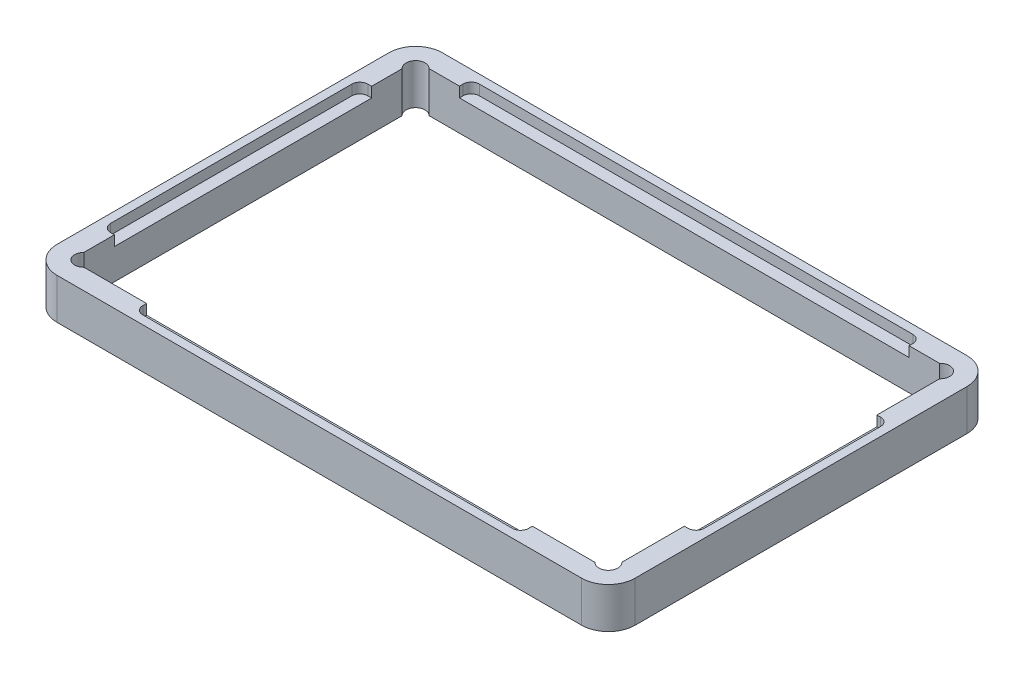
SolidWorks part; units mm, degrees
ref_plane "Front" through (0, 0, 0) normal (0, 0, 1) x (1, 0, 0)
ref_plane "Top" through (0, 0, 0) normal (0, 1, 0) x (1, 0, 0)
ref_plane "Right" through (0, 0, 0) normal (1, 0, 0) x (0, 0, -1)
sketch "Sketch1" plane through (0, 0, 0) normal (0, 1, 0) x (1, 0, 0)
  line L0 (-45, 0) -> (45, 0) construction
  line L1 (-45, 30) -> (45, 30) construction
  line L2 (-45, 30) -> (-45, -30) construction
  line L3 (-45, -30) -> (45, -30) construction
  line L4 (45, 30) -> (45, -30) construction
  line L5 (0, -30) -> (0, 30) construction
  line L6 (41.825, 26.825) -> (41.825, -26.825) construction
  line L7 (-41.825, -26.825) -> (41.825, -26.825) construction
  line L8 (-41.825, 26.825) -> (-41.825, -26.825) construction
  line L9 (-41.825, 26.825) -> (41.825, 26.825) construction
  line L10 (40.825, 25.825) -> (40.825, -25.825) construction
  line L11 (-40.825, -25.825) -> (40.825, -25.825) construction
  line L12 (-40.825, 25.825) -> (-40.825, -25.825) construction
  line L13 (-40.825, 25.825) -> (40.825, 25.825) construction
  line L14 (40.825, 21.65) -> (45, 21.65) construction
  line L15 (40.825, -21.65) -> (45, -21.65) construction
  line L16 (36.65, -25.825) -> (36.65, -30) construction
  line L17 (-36.65, -25.825) -> (-36.65, -30) construction
  line L18 (-40.825, -21.65) -> (-45, -21.65) construction
  line L19 (-36.65, 25.825) -> (-36.65, 30) construction
  line L20 (-40.825, 21.65) -> (-45, 21.65) construction
  line L21 (36.65, 25.825) -> (36.65, 30) construction
  line L22 (40.825, -25.825) -> (41.825, -25.825) construction
  circle A0 centre (-40.825, -25.825) radius 1 construction
  circle A1 centre (40.825, -25.825) radius 1 construction
  circle A2 centre (40.825, 25.825) radius 1 construction
  circle A3 centre (-40.825, 25.825) radius 1 construction
  circle A4 centre (40.825, -25.825) radius 4.175 construction
  circle A5 centre (40.825, 25.825) radius 4.175 construction
  circle A6 centre (-40.825, 25.825) radius 4.175 construction
  circle A7 centre (-40.825, -25.825) radius 4.175 construction
  dimension "D1" = 90
  dimension "D2" = 60
  dimension "D4" = 1
  dimension "D3" = 3.175
sketch "Sketch2" plane through (0, 0, 0) normal (0, 1, 0) x (1, 0, 0)
  line L0 (-45, 30) -> (-45, -30) construction
  line L1 (-45, -30) -> (45, -30) construction
  line L2 (45, 30) -> (45, -30) construction
  line L3 (-45, 30) -> (45, 30) construction
  line L12 (-41.825, -25.825) -> (-41.825, 25.825)
  line L13 (-40.825, 26.825) -> (40.825, 26.825)
  line L14 (41.825, 25.825) -> (41.825, -25.825)
  line L15 (40.825, -26.825) -> (-40.825, -26.825)
  line L16 (-45, 25.825) -> (-45, -25.825)
  line L17 (-40.825, -30) -> (40.825, -30)
  line L18 (45, 25.825) -> (45, -25.825)
  line L19 (-40.825, 30) -> (40.825, 30)
  circle A0 centre (40.825, 25.825) radius 4.175 construction
  circle A1 centre (40.825, 25.825) radius 1 construction
  circle A2 centre (-40.825, 25.825) radius 4.175 construction
  circle A3 centre (-40.825, 25.825) radius 1 construction
  arc A6 (45, 25.825) -> (40.825, 30) centre (40.825, 25.825) ccw
  arc A7 (41.825, 25.825) -> (40.825, 26.825) centre (40.825, 25.825) ccw
  arc A8 (-40.825, 30) -> (-45, 25.825) centre (-40.825, 25.825) ccw
  arc A9 (-40.825, 26.825) -> (-41.825, 25.825) centre (-40.825, 25.825) ccw
  circle A12 centre (-40.825, -25.825) radius 1 construction
  circle A13 centre (40.825, -25.825) radius 1 construction
  arc A14 (-41.825, -25.825) -> (-40.825, -26.825) centre (-40.825, -25.825) ccw
  arc A15 (40.825, -26.825) -> (41.825, -25.825) centre (40.825, -25.825) ccw
  arc A17 (-45, -25.825) -> (-40.825, -30) centre (-40.825, -25.825) ccw
  arc A18 (40.825, -30) -> (45, -25.825) centre (40.825, -25.825) ccw
extrude "Boss-Extrude3" add sketch "Sketch2" along normal blind 6.35
sketch "Sketch5" plane through (0, 0, 0) normal (0, -1, 0) x (1, 0, 0)
  circle A0 centre (-40.825, 25.825) radius 1.4224 construction
  circle A1 centre (-40.825, 25.825) radius 1.4224
  circle A2 centre (40.825, 25.8149) radius 1.4732 construction
  circle A3 centre (40.825, -25.825) radius 1.4732 construction
  circle A4 centre (-40.825, -25.8136) radius 1.4732 construction
  circle A5 centre (40.825, 25.8149) radius 1.4732
  circle A6 centre (40.825, -25.825) radius 1.4732
  circle A7 centre (-40.825, -25.8136) radius 1.4732
extrude "Cut-Extrude2" cut sketch "Sketch5" against normal through all
sketch "Sketch7" plane through (0, 6.35, 0) normal (0, 1, 0) x (1, 0, 0)
  line L0 (-33.7539, 28.4074) -> (33.7432, 28.4074) construction
  line L1 (34.7432, 26.0649) -> (34.7432, 27.4074) construction
  line L2 (-34.7539, 26.0649) -> (34.7432, 26.0649) construction
  line L3 (-34.7539, 27.4074) -> (-34.7539, 26.0649) construction
  line L4 (-41.075, 19.7216) -> (-42.4125, 19.7216) construction
  line L5 (-41.075, 19.7216) -> (-41.075, -19.8236) construction
  line L6 (-41.075, -19.8236) -> (-42.4125, -19.8236) construction
  line L7 (-43.4125, -18.8236) -> (-43.4125, 18.7216) construction
  line L8 (41.075, 14.7331) -> (42.4125, 14.7331) construction
  line L9 (43.4125, 13.7331) -> (43.4125, -13.7432) construction
  line L10 (42.4125, -14.7432) -> (41.075, -14.7432) construction
  line L11 (41.075, -14.7432) -> (41.075, 14.7331) construction
  line L13 (29.7526, -26.0851) -> (-29.8135, -26.0851) construction
  line L14 (-29.8135, -26.0851) -> (-29.8135, -27.4176) construction
  line L15 (-28.8135, -28.4176) -> (28.7526, -28.4176) construction
  line L16 (29.7526, -26.0851) -> (29.7526, -27.4176) construction
  line L18 (-41.075, -0.051) -> (41.075, -0.0051) construction
  line L19 (-0.0053, 26.0649) -> (-0.0304, -26.0851) construction
  line L20 (-35.0039, 27.4074) -> (-35.0039, 25.8149)
  line L21 (-35.0039, 25.8149) -> (34.9932, 25.8149)
  line L22 (34.9932, 25.8149) -> (34.9932, 27.4074)
  line L23 (-33.7539, 28.6574) -> (33.7432, 28.6574)
  line L24 (-43.6625, -18.8236) -> (-43.6625, 18.7216)
  line L25 (-40.825, -20.0736) -> (-42.4125, -20.0736)
  line L26 (-40.825, 19.9716) -> (-40.825, -20.0736)
  line L27 (-40.825, 19.9716) -> (-42.4125, 19.9716)
  line L28 (40.825, 14.9831) -> (42.4125, 14.9831)
  line L29 (43.6625, 13.7331) -> (43.6625, -13.7432)
  line L30 (42.4125, -14.9932) -> (40.825, -14.9932)
  line L31 (40.825, -14.9932) -> (40.825, 14.9831)
  line L32 (-28.8135, -28.6676) -> (28.7526, -28.6676)
  line L33 (-30.0635, -25.8351) -> (-30.0635, -27.4176)
  line L34 (30.0026, -25.8351) -> (-30.0635, -25.8351)
  line L35 (30.0026, -25.8351) -> (30.0026, -27.4176)
  arc A0 (33.7432, 28.4074) -> (34.7432, 27.4074) centre (33.7432, 27.4074) cw construction
  arc A1 (-33.7539, 28.4074) -> (-34.7539, 27.4074) centre (-33.7539, 27.4074) ccw construction
  arc A2 (-42.4125, 19.7216) -> (-43.4125, 18.7216) centre (-42.4125, 18.7216) ccw construction
  arc A3 (-42.4125, -19.8236) -> (-43.4125, -18.8236) centre (-42.4125, -18.8236) cw construction
  arc A4 (-29.8135, -27.4176) -> (-28.8135, -28.4176) centre (-28.8135, -27.4176) ccw construction
  arc A5 (29.7526, -27.4176) -> (28.7526, -28.4176) centre (28.7526, -27.4176) cw construction
  arc A6 (43.4125, -13.7432) -> (42.4125, -14.7432) centre (42.4125, -13.7432) cw construction
  arc A7 (42.4125, 14.7331) -> (43.4125, 13.7331) centre (42.4125, 13.7331) cw construction
  arc A8 (33.7432, 28.6574) -> (34.9932, 27.4074) centre (33.7432, 27.4074) cw
  arc A9 (-33.7539, 28.6574) -> (-35.0039, 27.4074) centre (-33.7539, 27.4074) ccw
  arc A10 (-42.4125, 19.9716) -> (-43.6625, 18.7216) centre (-42.4125, 18.7216) ccw
  arc A11 (-42.4125, -20.0736) -> (-43.6625, -18.8236) centre (-42.4125, -18.8236) cw
  arc A12 (42.4125, 14.9831) -> (43.6625, 13.7331) centre (42.4125, 13.7331) cw
  arc A13 (43.6625, -13.7432) -> (42.4125, -14.9932) centre (42.4125, -13.7432) cw
  arc A14 (30.0026, -27.4176) -> (28.7526, -28.6676) centre (28.7526, -27.4176) cw
  arc A15 (-30.0635, -27.4176) -> (-28.8135, -28.6676) centre (-28.8135, -27.4176) ccw
  dimension "D3" = 1
  dimension "D5" = 52.15
  dimension "D10" = 1
  dimension "D11" = 1
  dimension "D14" = 1
  dimension "D1" = 67.4971
  dimension "D2" = 69.4971
  dimension "D4" = 1.3426
  dimension "D6" = 82.15
  dimension "D7" = 37.5452
  dimension "D8" = 39.5452
  dimension "D9" = 1.3375
  dimension "D12" = 59.5661
  dimension "D13" = 57.5661
  dimension "D15" = 27.4763
  dimension "D16" = 29.4763
  dimension "D17" = 0.25
extrude "Cut-Extrude3" cut sketch "Sketch7" against normal blind 1.5875 contours L7 A2 L4 L5 L6 A3 | A1 L3 L2 L1 A0 L0 | L8 A7 L9 A6 L10 L11 | A5 L15 A4 L14 L13 L16 | L23 A8 L22 L21 L20 A9 | L31 L28 A12 L29 A13 L30 | L35 A14 L32 A15 L33 L34 | L26 L25 A11 L24 A10 L27
